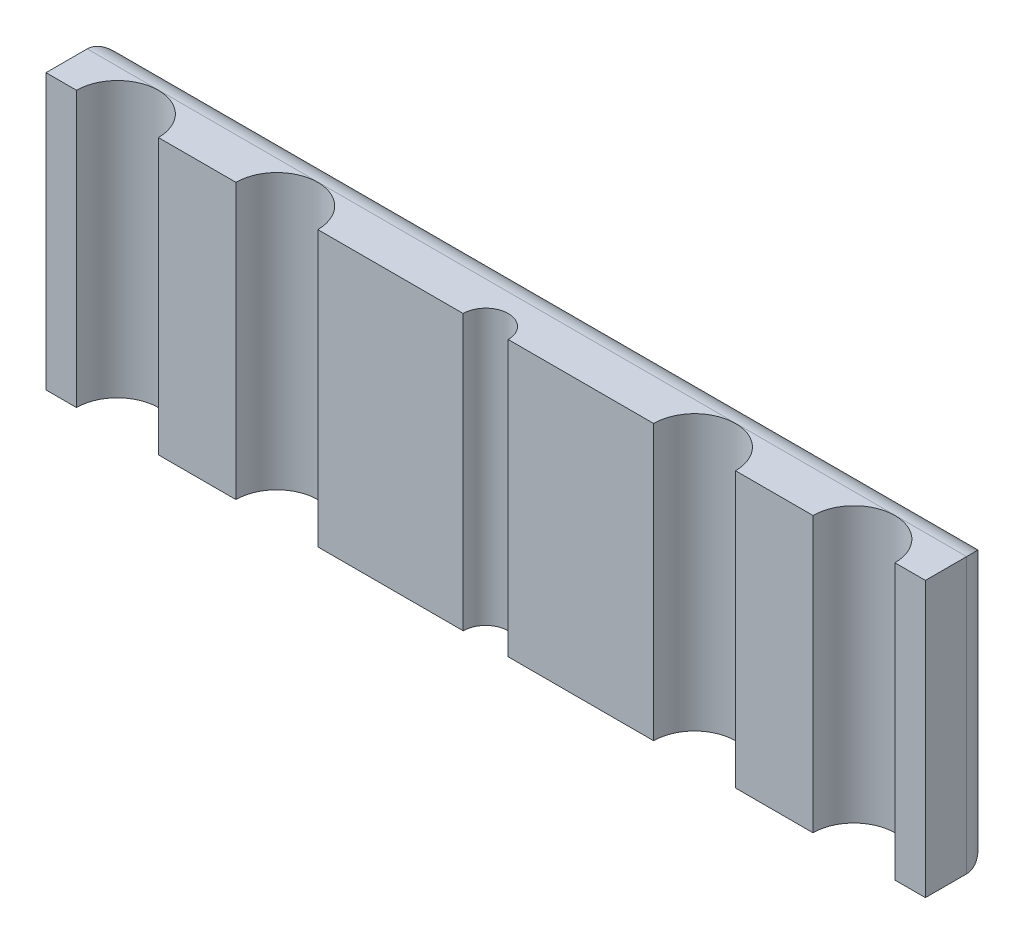
SolidWorks part; units mm, degrees
ref_plane "Front Plane" through (0, 0, 0) normal (0, 0, 1) x (1, 0, 0)
ref_plane "Top Plane" through (0, 0, 0) normal (0, 1, 0) x (1, 0, 0)
ref_plane "Right Plane" through (0, 0, 0) normal (1, 0, 0) x (0, 0, -1)
sketch "Esquisse1" plane through (0, 0, 0) normal (0, 0, 1) x (1, 0, 0)
  line L1 (0, 0) -> (-160, 0)
  line L2 (0, 0) -> (0, -50)
  line L3 (0, -50) -> (-160, -50)
  line L4 (-160, 0) -> (-160, -50)
  dimension "D1" = 160
  dimension "D2" = 50
extrude "Boss.-Extru.1" add sketch "Esquisse1" along normal blind 12.5
sketch "Esquisse2" plane through (0, 0, 0) normal (0, 1, 0) x (1, 0, 0)
  line L0 (0, -12.5) -> (-160, -12.5) construction
  line L1 (-160, -12.5) -> (-160, 0) construction
  line L2 (0, -12.5) -> (0, 0) construction
  circle A0 centre (-147, -12.5) radius 7.45
  circle A1 centre (-118, -12.5) radius 7.45
  circle A2 centre (-13, -12.5) radius 7.45
  circle A3 centre (-42, -12.5) radius 7.45
  circle A4 centre (-80, -12.5) radius 4.1
  dimension "D1" = 14.9
  dimension "D2" = 14.9
  dimension "D3" = 14.9
  dimension "D4" = 14.9
  dimension "D5" = 13
  dimension "D6" = 29
  dimension "D7" = 13
  dimension "D8" = 29
  dimension "D9" = 76
  dimension "D10" = 8.2
  dimension "D11" = 38
extrude "Enlèv. mat.-Extru.1" cut sketch "Esquisse2" against normal through all
fillet "Congé1" radius 5 4 edges at (0, -25, 0) (-80, 0, 0) (-80, -50, 0) (-160, -25, 0)
